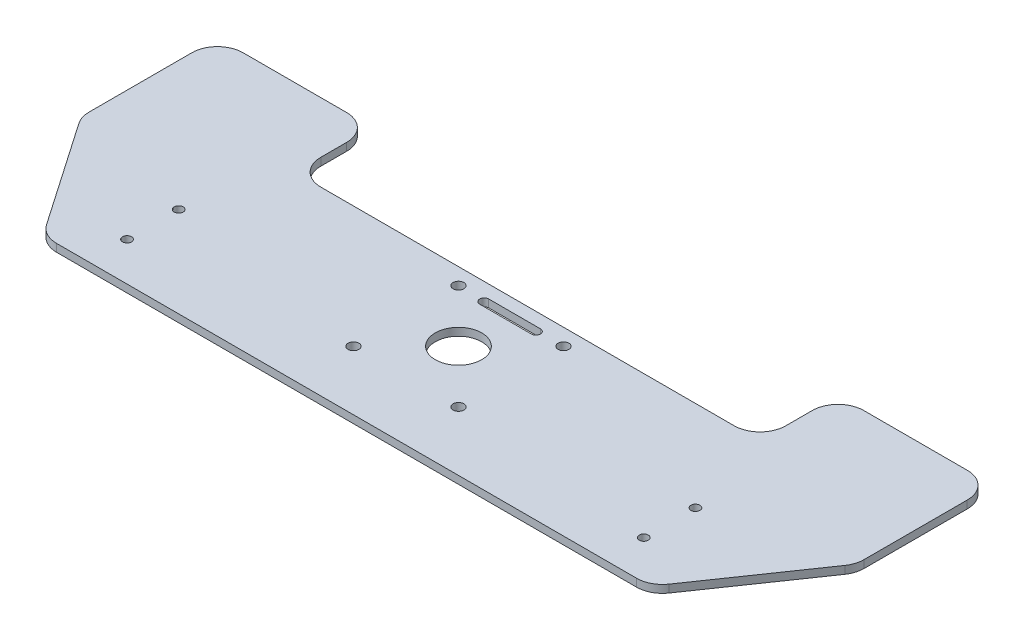
SolidWorks part; units mm, degrees
ref_plane "前视基准面" through (0, 0, 0) normal (0, 0, 1) x (1, 0, 0)
ref_plane "上视基准面" through (0, 0, 0) normal (0, 1, 0) x (1, 0, 0)
ref_plane "右视基准面" through (0, 0, 0) normal (1, 0, 0) x (0, 0, -1)
other "Configuration Table"
sketch "草图1" plane through (0, 0, 0) normal (0, 1, 0) x (1, 0, 0)
  line L5 (-148.2358, 19.5134) -> (-120.4921, -20.7712)
  line L6 (-150, 25.1854) -> (-150, 65)
  line L8 (0, 0) -> (0, 50000) construction
  line L13 (-140.0992, 74.9008) -> (-100, 74.9008)
  line L14 (0, 0.3213) -> (-0.1034, 0.2697) construction
  line L15 (-150, 74.9008) -> (-146.0376, 72.9222) construction
  line L16 (-90, 64.9008) -> (-90, 54.9008)
  line L17 (-80, 44.9008) -> (80, 44.9008)
  line L18 (-112.2563, -25.0992) -> (112.2563, -25.0992)
  line L19 (149.8966, 75.1705) -> (145.9342, 73.1919) construction
  line L20 (0, 0.2309) -> (-0.1034, 0.2697) construction
  line L21 (90, 64.9008) -> (90, 54.9008)
  line L22 (140.1011, 75.0927) -> (100.0019, 75.0927)
  line L23 (150, 25.1854) -> (150, 65)
  line L24 (148.2358, 19.5134) -> (120.4921, -20.7712)
  arc A10 (-90, 54.9008) -> (-80, 44.9008) centre (-80, 54.9008) ccw
  arc A11 (-90, 64.9008) -> (-100, 74.9008) centre (-100, 64.9008) ccw
  arc A12 (-150, 65) -> (-140.0992, 74.9008) centre (-140.0992, 65) cw
  arc A13 (-148.2358, 19.5134) -> (-150, 25.1854) centre (-140, 25.1854) cw
  arc A14 (-120.4921, -20.7712) -> (-112.2563, -25.0992) centre (-112.2563, -15.0992) ccw
  arc A15 (120.4921, -20.7712) -> (112.2563, -25.0992) centre (112.2563, -15.0992) cw
  arc A16 (148.2358, 19.5134) -> (150, 25.1854) centre (140, 25.1854) ccw
  arc A17 (150, 65) -> (140.1011, 75.0927) centre (140.1011, 65.1919) ccw
  arc A18 (90, 64.9008) -> (100.0019, 75.0927) centre (99.9982, 65.0927) cw
  arc A19 (90, 54.9008) -> (80, 44.9008) centre (80, 54.9008) cw
  point P0 (0, 0)
  point P17 (0, 25.2697)
  point P39 (0, 44.9008)
  point P40 (0, -25.0992)
  dimension "D1" = 60
extrude "凸台-拉伸1" add sketch "草图1" along normal blind 3
sketch "草图2" plane through (0, 3, 0) normal (0, 1, 0) x (1, 0, 0)
  line L1 (102.5393, 24.9008) -> (97.4607, 24.9008) construction
  line L2 (100, 24.9008) -> (100, -49975.0992) construction
  line L3 (-112.2563, -25.0992) -> (112.2563, -25.0992) construction
  line L4 (0, 0) -> (0, 50000) construction
  circle A0 centre (100, 9.9008) radius 1.75
  circle A1 centre (100, -10.0992) radius 1.75
  circle A2 centre (-100, -10.0992) radius 1.75
  circle A3 centre (-100, 9.9008) radius 1.75
  point P8 (100, 24.9008)
  dimension "D1" = 3.5
  dimension "D3" = 3.5
  dimension "D4" = 15
  dimension "D2" = 15
extrude "切除-拉伸1" cut sketch "草图2" against normal blind 10
sketch "草图3" plane through (0, 3, 0) normal (0, 1, 0) x (1, 0, 0)
  line L0 (-10, 38.1508) -> (10, 38.1508) construction
  line L1 (-10, 39.9008) -> (10, 39.9008)
  line L2 (-10, 36.4008) -> (10, 36.4008)
  line L3 (0, 0) -> (0, 50000) construction
  line L4 (80, 44.9008) -> (-80, 44.9008) construction
  arc A0 (-10, 39.9008) -> (-10, 36.4008) centre (-10, 38.1508) ccw
  arc A1 (10, 36.4008) -> (10, 39.9008) centre (10, 38.1508) ccw
  point P2 (0, 38.1508)
  dimension "D1" = 1.75
  dimension "D2" = 20
  dimension "D3" = 5
extrude "切除-拉伸2" cut sketch "草图3" against normal blind 3
sketch "草图4" plane through (0, 3, 0) normal (0, 1, 0) x (1, 0, 0)
  line L1 (-28.2843, 46.4693) -> (0, 18.1851) construction
  line L3 (0, 18.1851) -> (-28.2843, -10.0992) construction
  circle A0 centre (0, 18.1851) radius 9
  dimension "D1" = 18
extrude "切除-拉伸3" cut sketch "草图4" against normal blind 10
sketch "草图5" plane through (0, 0, 0) normal (0, -1, 0) x (1, 0, 0)
  circle A0 centre (-20.3235, 2.1384) radius 2.1
  circle A1 centre (20.3235, 2.1384) radius 2.1
  circle A2 centre (20.3235, -38.5085) radius 2.1
  circle A3 centre (-20.3235, -38.5085) radius 2.1
  point P11 (0, -18.1851)
  dimension "D1" = 4.2
  dimension "D2" = 4
extrude "切除-拉伸4" cut sketch "草图5" against normal blind 4
